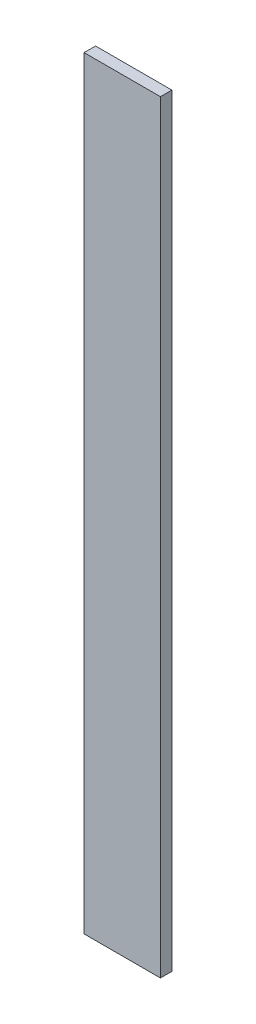
SolidWorks part; units mm, degrees
ref_plane "Front Plane" through (0, 0, 0) normal (0, 0, 1) x (1, 0, 0)
ref_plane "Top Plane" through (0, 0, 0) normal (0, 1, 0) x (1, 0, 0)
ref_plane "Right Plane" through (0, 0, 0) normal (1, 0, 0) x (0, 0, -1)
sketch "Sketch1" plane through (0, 0, 0) normal (0, 0, 1) x (1, 0, 0)
  line L1 (-56.5517, 297.7586) -> (-16.5517, 297.7586)
  line L2 (-56.5517, 297.7586) -> (-56.5517, -102.2414)
  line L3 (-56.5517, -102.2414) -> (-16.5517, -102.2414)
  line L4 (-16.5517, 297.7586) -> (-16.5517, -102.2414)
  dimension "D1" = 40
  dimension "D2" = 400
extrude "Boss-Extrude1" add sketch "Sketch1" along normal blind 6
